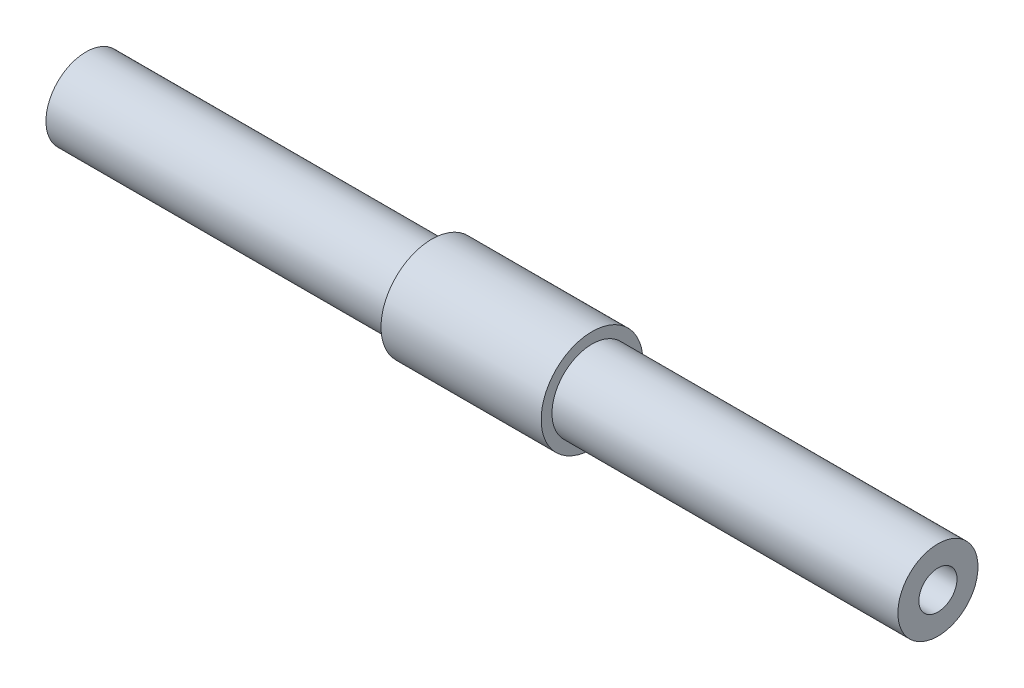
SolidWorks part; units mm, degrees
ref_plane "Alzado" through (0, 0, 0) normal (0, 0, 1) x (1, 0, 0)
ref_plane "Planta" through (0, 0, 0) normal (0, 1, 0) x (1, 0, 0)
ref_plane "Vista lateral" through (0, 0, 0) normal (1, 0, 0) x (0, 0, -1)
sketch "Croquis1" plane through (0, 0, 0) normal (0, 1, 0) x (1, 0, 0)
  line L0 (53.175, 0) -> (-53.175, 0)
  line L1 (-53.175, 0) -> (-53.175, 5)
  line L2 (-53.175, 5) -> (-10, 5)
  line L4 (53.175, 5) -> (9.995, 5)
  line L5 (53.175, 0) -> (53.175, 5)
  line L6 (9.995, 6.35) -> (-10, 6.35)
  line L7 (9.995, 6.35) -> (9.995, 5)
  line L8 (-10, 6.35) -> (-10, 5)
  point P4 (0, 0)
  dimension "D1" = 106.35
  dimension "D2" = 5
  dimension "D3" = 43.175
  dimension "D4" = 6.35
  dimension "D5" = 5
  dimension "D6" = 43.18
revolve "Revolución1" add sketch "Croquis1" angle 360 about L0
sketch "Croquis2" plane through (-53.175, 0, 0) normal (-1, 0, 0) x (0, 0, 1)
  circle A0 centre (0, 0) radius 2.3813
  dimension "D1" = 4.7625
extrude "Cortar-Extruir1" cut sketch "Croquis2" against normal blind 10
ref_plane "Plano1" through (3.175, 0, 0) normal (-1, 0, 0) x (0, 0, 1)
mirror "Simetría1" about plane through (3.175, 0, 0) normal (-1, 0, 0) of "Cortar-Extruir1"
